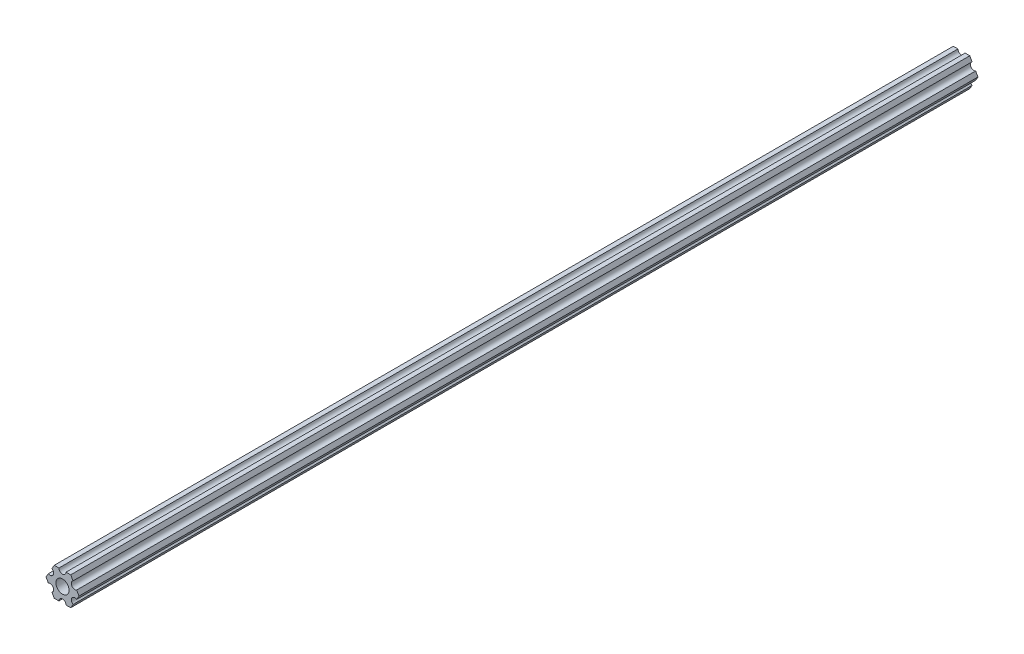
SolidWorks part; units mm, degrees
ref_plane "Front Plane" through (0, 0, 0) normal (0, 0, 1) x (1, 0, 0)
ref_plane "Top Plane" through (0, 0, 0) normal (0, 1, 0) x (1, 0, 0)
ref_plane "Right Plane" through (0, 0, 0) normal (1, 0, 0) x (0, 0, -1)
sketch "Sketch1" plane through (0, 0, 0) normal (0, 0, 1) x (1, 0, 0)
  line L0 (-1.5875, 6.35) -> (-3.6662, 6.35)
  line L1 (7.3323, 0) -> (6.293, 1.8002)
  line L2 (3.6662, 6.35) -> (1.5875, 6.35)
  line L3 (-3.6662, 6.35) -> (-4.7055, 4.5498)
  line L4 (-7.3323, 0) -> (-6.293, -1.8002)
  line L5 (-3.6662, -6.35) -> (-1.5875, -6.35)
  line L6 (3.6662, -6.35) -> (4.7055, -4.5498)
  line L7 (-6.293, 1.8002) -> (-7.3323, 0)
  line L8 (-4.7055, -4.5498) -> (-3.6662, -6.35)
  line L9 (1.5875, -6.35) -> (3.6662, -6.35)
  line L10 (6.293, -1.8002) -> (7.3323, 0)
  line L11 (4.7055, 4.5498) -> (3.6662, 6.35)
  circle A0 centre (0, 0) radius 2.9337
  arc A2 (-1.5875, 6.35) -> (1.5875, 6.35) centre (0, 6.35) ccw
  arc A3 (4.7055, 4.5498) -> (6.293, 1.8002) centre (5.4993, 3.175) ccw
  arc A4 (6.293, -1.8002) -> (4.7055, -4.5498) centre (5.4993, -3.175) ccw
  arc A5 (1.5875, -6.35) -> (-1.5875, -6.35) centre (0, -6.35) ccw
  arc A6 (-4.7055, -4.5498) -> (-6.293, -1.8002) centre (-5.4993, -3.175) ccw
  arc A7 (-6.293, 1.8002) -> (-4.7055, 4.5498) centre (-5.4993, 3.175) ccw
  dimension "D1" = 5.8674
  dimension "D3" = 3.175
  dimension "D4" = 6
extrude "Boss-Extrude1" add sketch "Sketch1" along normal blind 400.05
